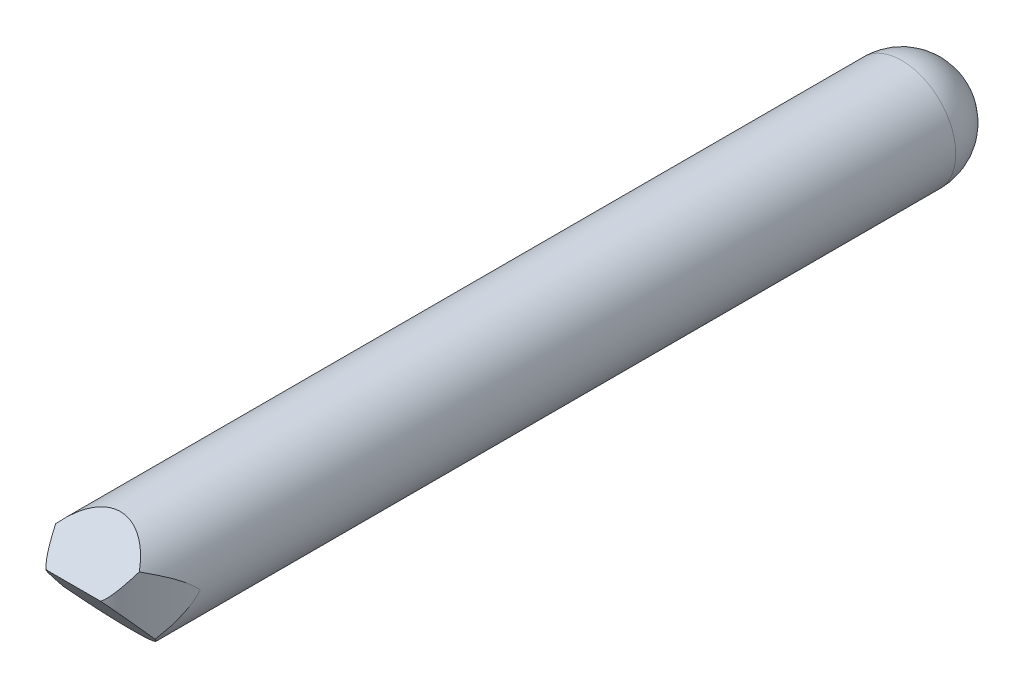
SolidWorks part; units mm, degrees
ref_plane "Front Plane" through (0, 0, 0) normal (0, 0, 1) x (1, 0, 0)
ref_plane "Top Plane" through (0, 0, 0) normal (0, 1, 0) x (1, 0, 0)
ref_plane "Right Plane" through (0, 0, 0) normal (1, 0, 0) x (0, 0, -1)
sketch "Sketch1" plane through (0, 0, 0) normal (0, 0, 1) x (1, 0, 0)
  circle A0 centre (0, 0) radius 152.4
  dimension "D1" = 304.8
extrude "Boss-Extrude1" add sketch "Sketch1" along normal blind 2494.28
sketch "Sketch3" plane through (0, 0, 0) normal (1, 0, 0) x (0, 0, -1)
  line L0 (-2361.3585, 152.4) -> (-2494.28, 37.7271)
  line L1 (0, 152.4) -> (-2494.28, 152.4) construction
  line L2 (-2494.28, 152.4) -> (-2494.28, -152.4) construction
  line L3 (-2494.28, 37.7271) -> (-2330.2552, -152.4)
  line L4 (-2494.28, -152.4) -> (0, -152.4) construction
  line L5 (-2330.2552, -152.4) -> (-2361.3585, 152.4) construction
  line L6 (-2361.3585, 152.4) -> (-2701.9786, 152.4)
  line L7 (-2701.9786, 152.4) -> (-2701.9786, -152.4)
  line L8 (-2701.9786, -152.4) -> (-2330.2552, -152.4)
extrude "Cut-Extrude1" cut sketch "Sketch3" against normal mid plane 406.4
ref_plane "Plane2" through (0, 0, 2330.2552) normal (0, 0, 1) x (1, 0, 0)
sketch "Sketch4" plane through (0, 0, 0) normal (0, 1, 0) x (1, 0, 0)
  line L0 (-76.2, -2494.28) -> (-152.4, -2288.4323) construction
  line L1 (-147.6564, -2494.28) -> (147.6564, -2494.28) construction
  line L3 (-152.4, 0) -> (-152.4, -2461.7324) construction
  line L5 (-274.6687, -2288.4323) -> (-274.6687, -2617.6298)
  line L6 (-274.6687, -2617.6298) -> (274.6687, -2617.6298)
  line L7 (274.6687, -2617.6298) -> (274.6687, -2288.4323)
  line L9 (152.4, -2288.4323) -> (76.2, -2494.28) construction
  line L10 (76.2, -2494.28) -> (-76.2, -2494.28)
  line L11 (152.4, -2461.7324) -> (152.4, 0) construction
  line L12 (0, -167.64) -> (0, 167.64) construction
  line L13 (-152.4, -2288.4323) -> (-274.6687, -2288.4323)
  line L14 (152.4, -2288.4323) -> (274.6687, -2288.4323)
  conic Q0 (-152.4, -2288.4323) -> (-76.2, -2494.28) control (-152.4, -2456.0689) rho 0.275484
  conic Q1 (152.4, -2288.4323) -> (76.2, -2494.28) control (152.4, -2456.0689) rho 0.275484
  point P4 (0, 0)
  point P8 (250.9017, -2617.6298)
  point P15 (290.1927, -2238.6346)
  point P16 (0, -2494.28)
  point P17 (-152.4, -2288.4323)
  dimension "D1" = 152.4
extrude "Cut-Extrude2" cut sketch "Sketch4" against normal mid plane 406.4
fillet "Fillet1" radius 152.4 1 edges at (152.4, 0, 0)
